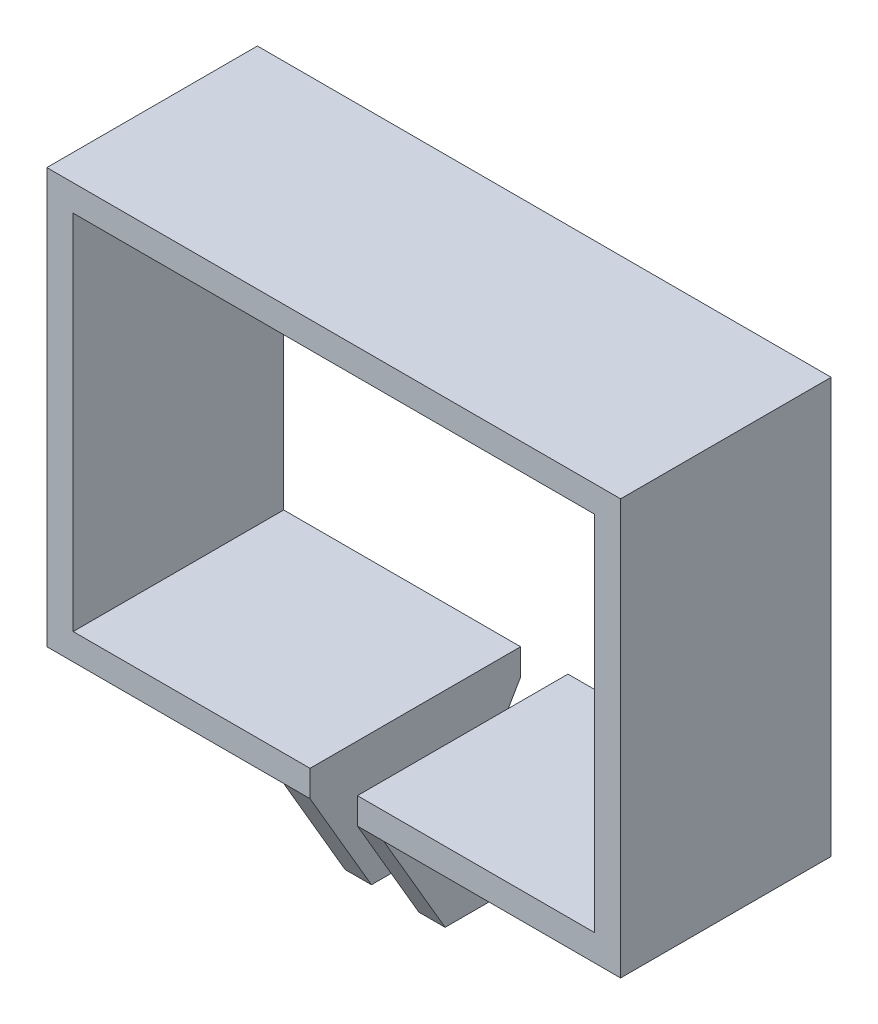
SolidWorks part; units mm, degrees
ref_plane "Plan de face" through (0, 0, 0) normal (0, 0, 1) x (1, 0, 0)
ref_plane "Plan de dessus" through (0, 0, 0) normal (0, 1, 0) x (1, 0, 0)
ref_plane "Plan de droite" through (0, 0, 0) normal (1, 0, 0) x (0, 0, -1)
sketch "Esquisse1" plane through (0, 0, 0) normal (0, 0, 1) x (1, 0, 0)
  line L0 (-29.7, -20.65) -> (-29.7, 20.65)
  line L1 (-29.7, 20.65) -> (29.7, 20.65)
  line L2 (29.7, 20.65) -> (29.7, -20.65)
  line L3 (29.7, -20.65) -> (2.7, -20.65)
  line L4 (2.7, -20.65) -> (2.7, -35.65)
  line L5 (-29.7, -20.65) -> (-2.7, -20.65)
  line L6 (-2.7, -20.65) -> (-2.7, -35.65)
  line L7 (-29.7, 20.65) -> (29.7, -20.65) construction
  dimension "D1" = 59.4
  dimension "D2" = 41.3
  dimension "D3" = 15
  dimension "D4" = 15
  dimension "D5" = 27
  dimension "D6" = 27
extrude "Extru.-Mince1" add sketch "Esquisse1" along normal blind 24 thin thin type one direction wall 3
sketch "Esquisse2" plane through (-5.7, 0, 0) normal (-1, 0, 0) x (0, 0, 1)
  line L0 (0, -23.65) -> (7, -35.65)
  line L1 (24, -35.65) -> (0, -35.65) construction
  line L2 (7, -35.65) -> (0, -35.65)
  line L3 (0, -35.65) -> (0, -23.65)
  line L4 (17, -35.65) -> (24, -35.65)
  line L5 (24, -35.65) -> (24, -23.65)
  line L6 (24, -23.65) -> (17, -35.65)
  circle A0 centre (12, -30.65) radius 2.25
  dimension "D5" = 4.5
  dimension "D1" = 7
  dimension "D2" = 7
  dimension "D3" = 12
  dimension "D4" = 5
extrude "Enlèv. mat.-Extru.1" cut sketch "Esquisse2" against normal blind 20
